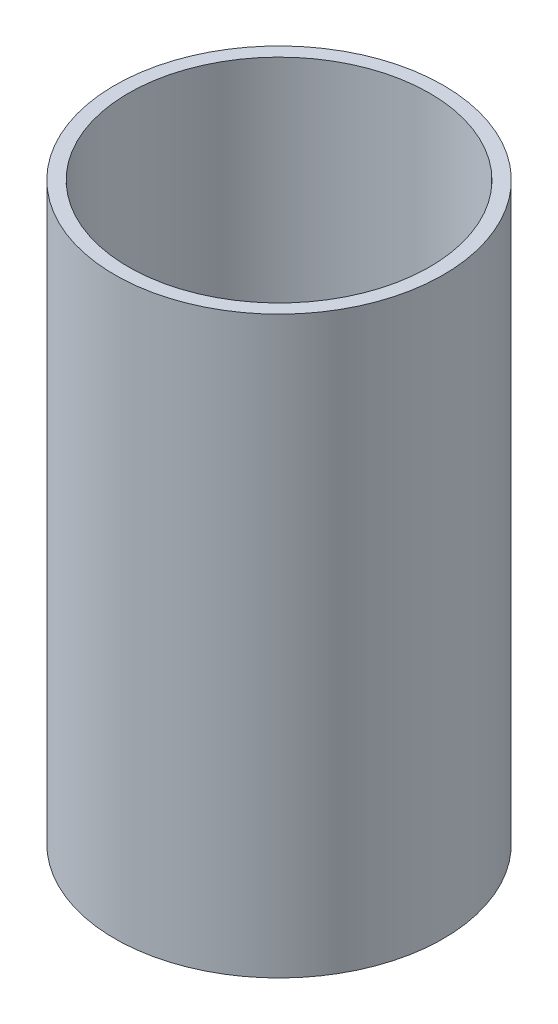
SolidWorks part; units mm, degrees
ref_plane "Front Plane" through (0, 0, 0) normal (0, 0, 1) x (1, 0, 0)
ref_plane "Top Plane" through (0, 0, 0) normal (0, 1, 0) x (1, 0, 0)
ref_plane "Right Plane" through (0, 0, 0) normal (1, 0, 0) x (0, 0, -1)
sketch "Sketch2" plane through (0, 0, 0) normal (0, 1, 0) x (1, 0, 0)
  circle A0 centre (0, 0) radius 11
  circle A1 centre (0, 0) radius 12
  dimension "D1" = 22
  dimension "D2" = 24
extrude "Boss-Extrude1" add sketch "Sketch2" along normal mid plane 42
